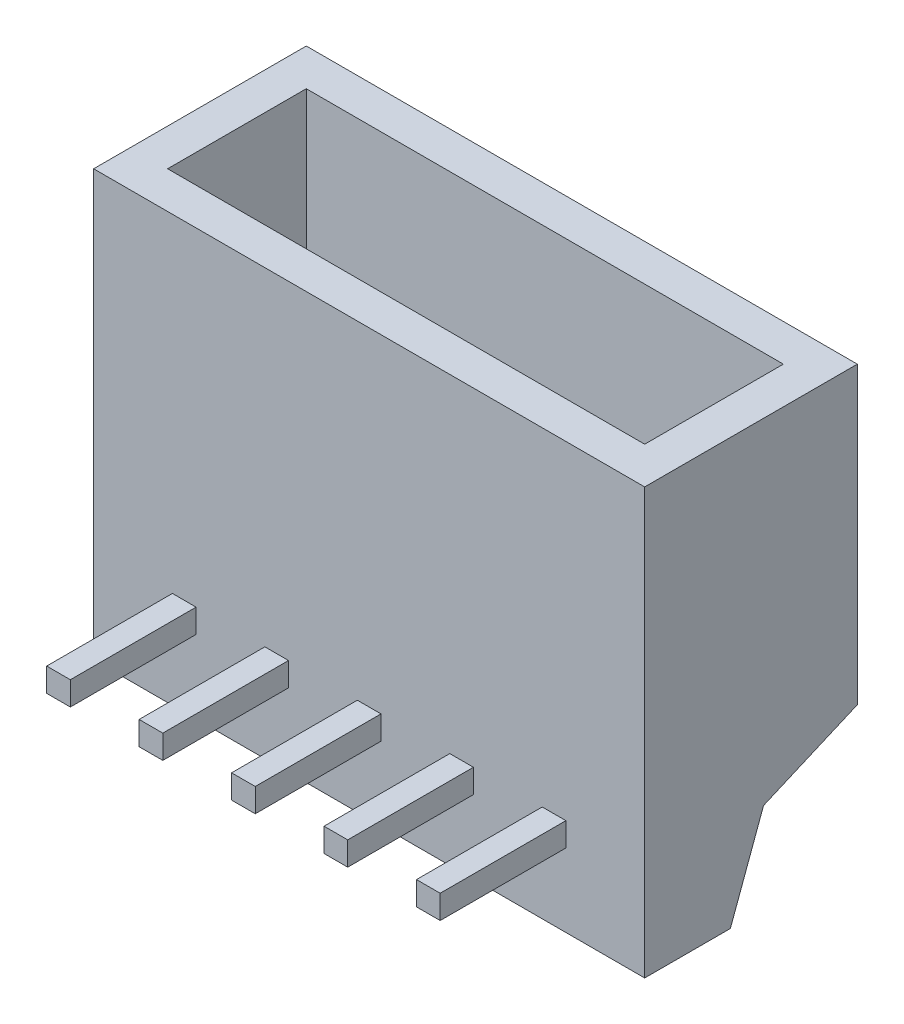
SolidWorks part; units mm, degrees
ref_plane "Спереди" through (0, 0, 0) normal (0, 0, 1) x (1, 0, 0)
ref_plane "Сверху" through (0, 0, 0) normal (0, 1, 0) x (1, 0, 0)
ref_plane "Справа" through (0, 0, 0) normal (1, 0, 0) x (0, 0, -1)
sketch "Эскиз1" plane through (0, 0, 0) normal (0, 0, 1) x (1, 0, 0)
  line L1 (0, 0) -> (14.9, 0)
  line L2 (0, 0) -> (0, 11.5)
  line L3 (0, 11.5) -> (14.9, 11.5)
  line L4 (14.9, 0) -> (14.9, 11.5)
  dimension "D1" = 11.5
  dimension "D2" = 14.9
extrude "Бобышка-Вытянуть1" add sketch "Эскиз1" along normal blind 5.75
sketch "Эскиз2" plane through (0, 0, 5.75) normal (0, 0, 1) x (1, 0, 0)
  line L0 (4.63, 1.98) -> (5.27, 1.98)
  line L1 (2.13, 1.98) -> (2.77, 1.98)
  line L2 (2.13, 1.98) -> (2.13, 2.62)
  line L3 (2.13, 2.62) -> (2.77, 2.62)
  line L4 (2.77, 1.98) -> (2.77, 2.62)
  line L5 (4.63, 1.98) -> (4.63, 2.62)
  line L6 (4.63, 2.62) -> (5.27, 2.62)
  line L7 (5.27, 1.98) -> (5.27, 2.62)
  line L8 (7.13, 1.98) -> (7.77, 1.98)
  line L9 (7.13, 1.98) -> (7.13, 2.62)
  line L10 (7.13, 2.62) -> (7.77, 2.62)
  line L11 (7.77, 1.98) -> (7.77, 2.62)
  line L12 (9.63, 1.98) -> (10.27, 1.98)
  line L13 (9.63, 1.98) -> (9.63, 2.62)
  line L14 (9.63, 2.62) -> (10.27, 2.62)
  line L15 (10.27, 1.98) -> (10.27, 2.62)
  line L16 (12.13, 1.98) -> (12.77, 1.98)
  line L17 (12.13, 1.98) -> (12.13, 2.62)
  line L18 (12.13, 2.62) -> (12.77, 2.62)
  line L19 (12.77, 1.98) -> (12.77, 2.62)
  line L20 (7.45, 11.5) -> (7.45, 0) construction
  line L21 (14.9, 11.5) -> (0, 11.5) construction
  line L22 (0, 0) -> (14.9, 0) construction
  point P26 (7.45, 2.62)
  point P27 (7.77, 2.3)
  dimension "D1" = 0.64
  dimension "D2" = 0.64
  dimension "D4" = 9.2
  dimension "D3" = 5
extrude "Бобышка-Вытянуть2" add sketch "Эскиз2" along normal blind 3.4
sketch "Эскиз3" plane through (0, 0, 0) normal (-1, 0, 0) x (0, 0, 1)
  line L0 (0, 0) -> (0, 3.5238)
  line L1 (0, 11.5) -> (0, 0) construction
  line L2 (0, 3.5238) -> (2.5364, 2.4311)
  line L3 (2.5364, 2.4311) -> (3.4334, 0)
  line L4 (5.75, 0) -> (0, 0) construction
  line L5 (3.4334, 0) -> (0, 0)
extrude "Вырез-Вытянуть1" cut sketch "Эскиз3" against normal through all
sketch "Эскиз4" plane through (0, 11.5, 0) normal (0, 1, 0) x (1, 0, 0)
  line L8 (13.9, -1) -> (1, -1)
  line L9 (1, -1) -> (1, -4.75)
  line L10 (1, -4.75) -> (13.9, -4.75)
  line L11 (13.9, -4.75) -> (13.9, -1)
  line L12 (13.9, -1) -> (1, -1)
  line L13 (1, -1) -> (1, -4.75)
  line L14 (1, -4.75) -> (13.9, -4.75)
  line L15 (13.9, -4.75) -> (13.9, -1)
  dimension "D1" = 1
extrude "Вырез-Вытянуть2" cut sketch "Эскиз4" against normal blind 5
ref_plane "Плоскость1" through (7.45, 0, 0) normal (-1, 0, 0) x (0, 0, 1)
